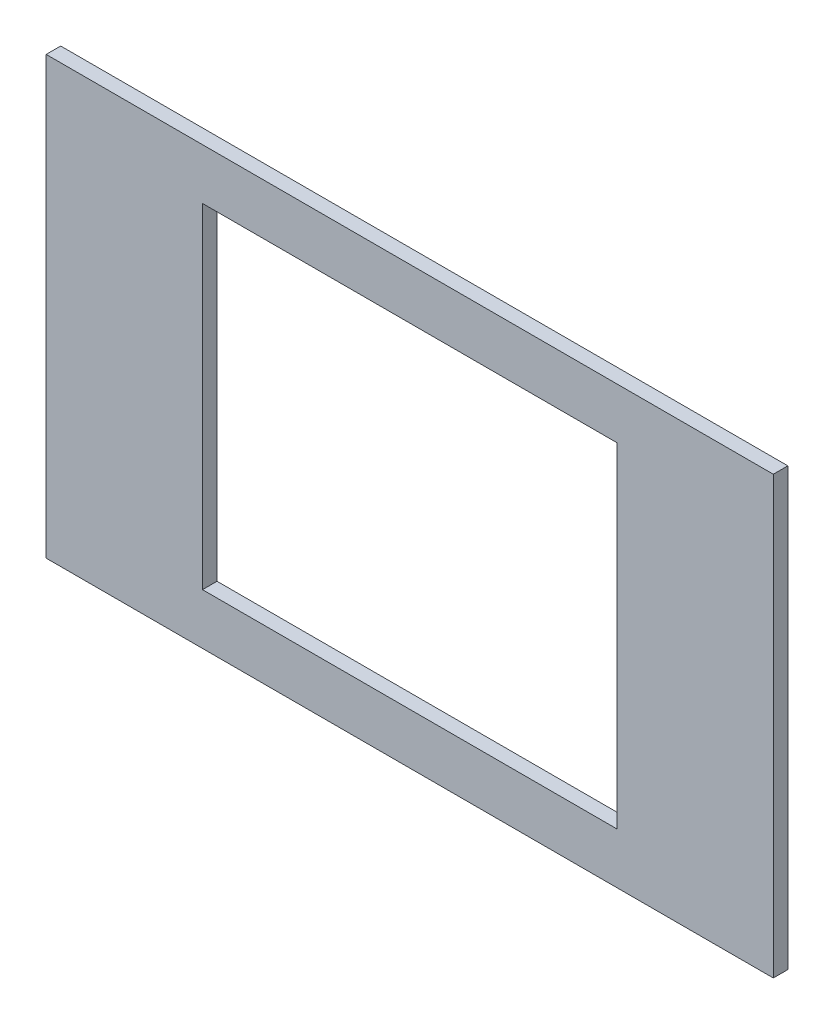
SolidWorks part; units mm, degrees
ref_plane "Front Plane" through (0, 0, 0) normal (0, 0, 1) x (1, 0, 0)
ref_plane "Top Plane" through (0, 0, 0) normal (0, 1, 0) x (1, 0, 0)
ref_plane "Right Plane" through (0, 0, 0) normal (1, 0, 0) x (0, 0, -1)
sketch "Sketch1" plane through (0, 0, 0) normal (0, 0, 1) x (1, 0, 0)
  line L1 (-63.5, -38.1) -> (63.5, -38.1)
  line L2 (-63.5, -38.1) -> (-63.5, 38.1)
  line L3 (-63.5, 38.1) -> (63.5, 38.1)
  line L4 (63.5, -38.1) -> (63.5, 38.1)
  line L5 (-63.5, -38.1) -> (63.5, 38.1) construction
  line L6 (-63.5, 38.1) -> (63.5, -38.1) construction
  point P0 (0, 0)
extrude "main body" add sketch "Sketch1" along normal blind 2.54
sketch "Sketch2" plane through (0, 0, 2.54) normal (0, 0, 1) x (1, 0, 0)
  line L1 (-36.195, -29.21) -> (36.195, -29.21)
  line L2 (-36.195, -29.21) -> (-36.195, 29.21)
  line L3 (-36.195, 29.21) -> (36.195, 29.21)
  line L4 (36.195, -29.21) -> (36.195, 29.21)
  line L5 (-36.195, -29.21) -> (36.195, 29.21) construction
  line L6 (-36.195, 29.21) -> (36.195, -29.21) construction
  point P0 (0, 0)
  dimension "D1" = 58.42
  dimension "D2" = 72.39
extrude "hole for circuitboard" cut sketch "Sketch2" against normal blind 2.54
